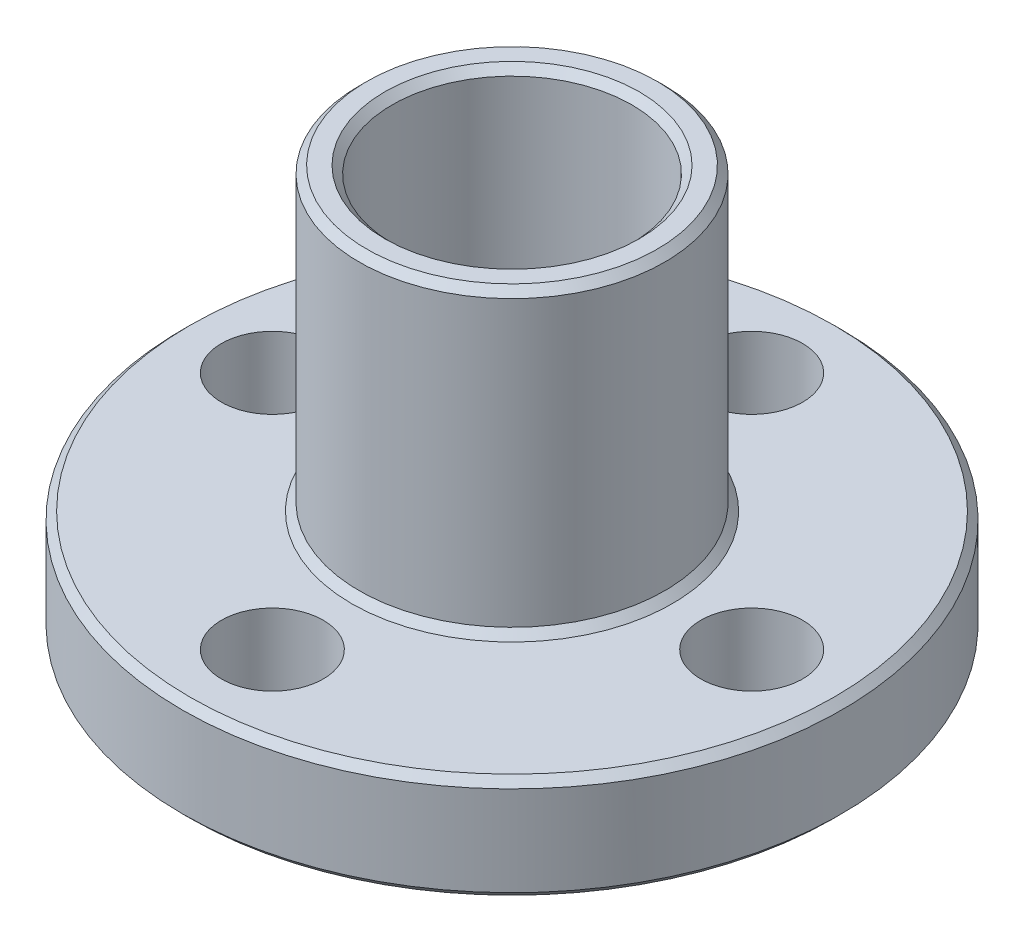
SolidWorks part; units mm, degrees
ref_plane "Front Plane" through (0, 0, 0) normal (0, 0, 1) x (1, 0, 0)
ref_plane "Top Plane" through (0, 0, 0) normal (0, 1, 0) x (1, 0, 0)
ref_plane "Right Plane" through (0, 0, 0) normal (1, 0, 0) x (0, 0, -1)
sketch "Sketch1" plane through (0, 0, 0) normal (0, 0, 1) x (1, 0, 0)
  line L0 (0, 0) -> (0, -14896.8634) construction
  line L1 (0, 0) -> (5.1, 0)
  line L2 (5.1, 0) -> (5.1, 1.5)
  line L3 (5.1, 1.5) -> (11, 1.5)
  line L4 (11, 1.5) -> (11, 5)
  line L5 (11, 5) -> (5.1, 5)
  line L6 (5.1, 5) -> (5.1, 15)
  line L7 (5.1, 15) -> (0, 15)
  line L8 (0, 15) -> (0, 0)
  dimension "D1" = 5.1
  dimension "D2" = 10
  dimension "D3" = 3.5
  dimension "D4" = 15
  dimension "D5" = 11
revolve "Revolve1" add sketch "Sketch1" angle 360 about L0
sketch "Sketch2" plane through (0, 0, 0) normal (0, -1, 0) x (1, 0, 0)
  circle A0 centre (0, 0) radius 4
  dimension "D1" = 8
extrude "Cut-Extrude1" cut sketch "Sketch2" against normal through all both and the other way through all
sketch "Sketch3" plane through (0, 1.5, 0) normal (0, -1, 0) x (1, 0, 0)
  point P0 (0, 8)
  point P6 (8, 0)
  point P7 (0, -8)
  point P8 (-8, 0)
  point P9 (0, 0)
  dimension "D2" = 4
  dimension "D1" = 8
hole_wizard "M3 Clearance Hole1" positions "Sketch3" profile "Sketch4" hole size "M3" standard "ANSI Metric"
sketch "Sketch4" plane through (0, 1.5, 8) normal (1, 0, 0) x (0, 0, -1)
  line L0 (0, 0) -> (0, 11.0215)
  line L1 (0, 11.0215) -> (1.7, 10)
  line L2 (1.7, 10) -> (1.7, 0)
  line L5 (1.7, 0) -> (0, 0)
  line L10 (0, 11.0215) -> (-1.7, 10) construction
  line L11 (0, -6.35) -> (0, 107.95) construction
  dimension "Hole Dia." = 3.4
  dimension "Hole Depth" = 10
  dimension "Drill Angle" = 118
chamfer "Chamfer1" distance 0.25 angle 45 7 edges at (0, 5, 5.1) (0, 1.5, 5.1) (0, 0, 5.1) (0, 1.5, 11) (0, 5, 11) (0, 15, -4) (0, 15, 5.1)
